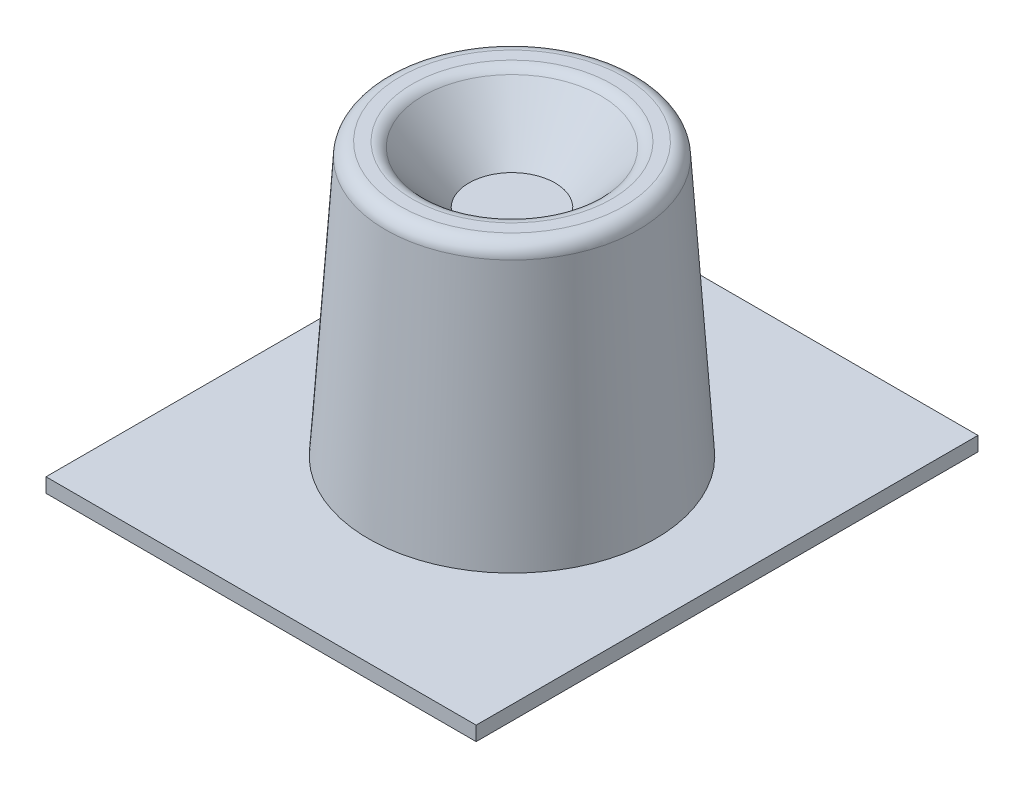
SolidWorks part; units mm, degrees
ref_plane "Plan de face" through (0, 0, 0) normal (0, 0, 1) x (1, 0, 0)
ref_plane "Plan de dessus" through (0, 0, 0) normal (0, 1, 0) x (1, 0, 0)
ref_plane "Plan de droite" through (0, 0, 0) normal (1, 0, 0) x (0, 0, -1)
sketch "Esquisse1" plane through (0, 0, 0) normal (0, 0, 1) x (1, 0, 0)
  line L0 (0, 0) -> (0, 31.75) construction
  line L1 (0, 19.1361) -> (3, 19.1361)
  line L2 (3, 19.1361) -> (6.5, 23.1361)
  line L3 (6.5, 23.1361) -> (8.75, 23.1361)
  line L4 (8.75, 23.1361) -> (10, 4.1361)
  line L5 (10, 4.1361) -> (0, 4.1361)
  line L6 (0, 4.1361) -> (0, 19.1361)
  dimension "D1" = 3
  dimension "D2" = 6.5
  dimension "D3" = 4
  dimension "D4" = 8.75
  dimension "D5" = 15
  dimension "D6" = 10
revolve "Révolution1" add sketch "Esquisse1" angle 360 about L0
fillet "Congé1" radius 1 2 edges at (0, 23.1361, -8.75) (0, 23.1361, -6.5)
sketch "Esquisse2" plane through (0, 4.1361, 0) normal (0, -1, 0) x (1, 0, 0)
  line L1 (15, -17.5) -> (-15, -17.5)
  line L2 (15, -17.5) -> (15, 17.5)
  line L3 (15, 17.5) -> (-15, 17.5)
  line L4 (-15, -17.5) -> (-15, 17.5)
  dimension "D1" = 35
  dimension "D2" = 17.5
  dimension "D3" = 30
  dimension "D4" = 15
extrude "Boss.-Extru.1" add sketch "Esquisse2" along normal blind 1
